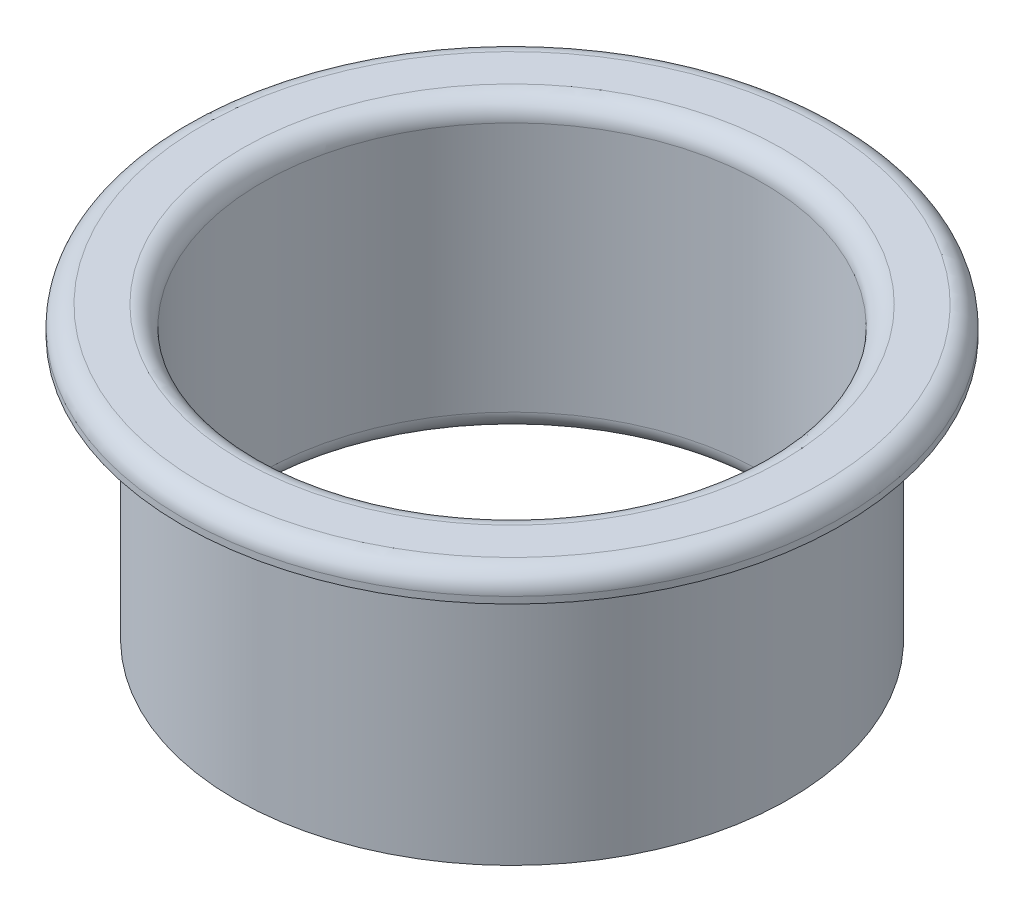
SolidWorks part; units mm, degrees
ref_plane "Front" through (0, 0, 0) normal (0, 0, 1) x (1, 0, 0)
ref_plane "Top" through (0, 0, 0) normal (0, 1, 0) x (1, 0, 0)
ref_plane "Right" through (0, 0, 0) normal (1, 0, 0) x (0, 0, -1)
sketch "Sketch1" plane through (0, 0, 0) normal (0, 1, 0) x (1, 0, 0)
  circle A0 centre (0, 0) radius 10.5
  circle A1 centre (0, 0) radius 9.5
  dimension "D1" = 21
  dimension "D2" = 1
extrude "Boss-Extrude1" add sketch "Sketch1" against normal blind 10
sketch "Sketch2" plane through (0, 0, 0) normal (0, 1, 0) x (1, 0, 0)
  circle A1 centre (0, 0) radius 9.5
  circle A2 centre (0, 0) radius 12.5
  circle A3 centre (0, 0) radius 12.5
  dimension "D1" = 2
  dimension "D2" = 3
extrude "Boss-Extrude2" add sketch "Sketch2" along normal blind 1
fillet "Fillet1" radius 0.75 4 edges at (0, 1, 9.5) (0, 0, 10.5) (0, 1, 12.5) (0, -10, 9.5)
